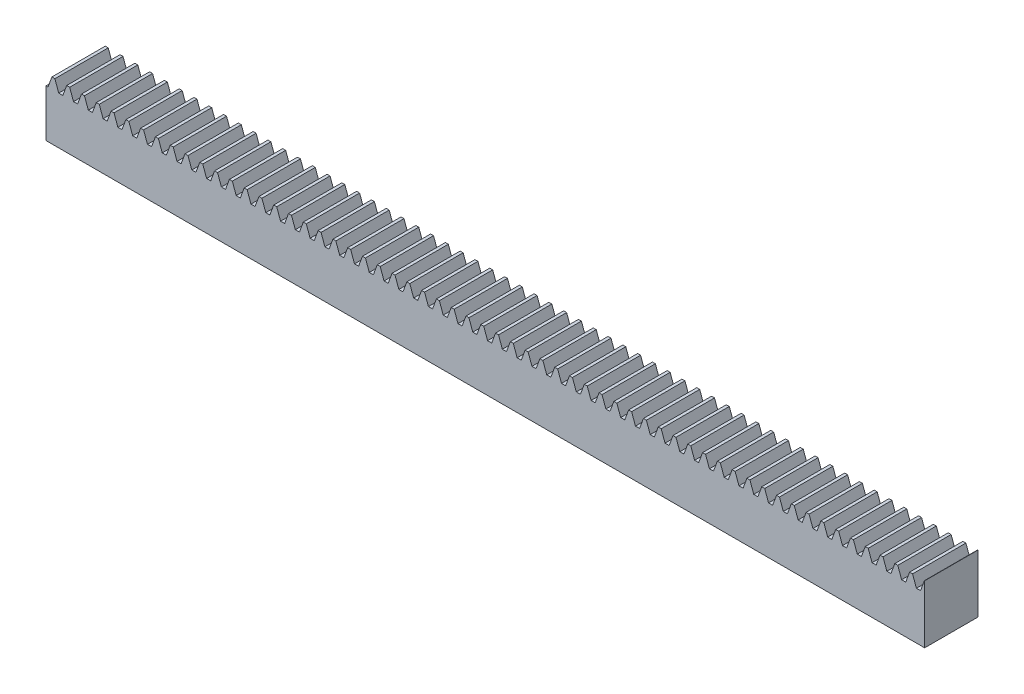
SolidWorks part; units mm, degrees
extrude "Blank" add sketch "BlankSke" against normal blind 17
sketch "BlankSke" plane through (0, 0, 0) normal (0, 0, 1) x (1, 0, 0)
  line L1 (0, 0) -> (280, 0)
  line L2 (0, 0) -> (0, 18.5)
  line L3 (0, 18.5) -> (280, 18.5)
  line L4 (280, 0) -> (280, 18.5)
  dimension "Length" = 280
  dimension "Blank_height" = 18.5
ref_plane "Plane1" through (0, 0, 0) normal (0, 0, 1) x (1, 0, 0)
ref_plane "Plane2" through (0, 0, 0) normal (0, 1, 0) x (1, 0, 0)
ref_plane "Plane3" through (0, 0, 0) normal (1, 0, 0) x (0, 0, -1)
sketch "HoldingSke" plane through (0, 0, 0) normal (0, 1, 0) x (1, 0, 0)
  line L0 (0, 0) -> (0.0928, 0.6602)
  line L1 (-15, 0) -> (100, 0) construction
  line L2 (0, 0) -> (-2.1039, 2.3779)
  line L3 (0, 0) -> (-11.863, 4.5341)
  line L4 (0, 0) -> (4.1868, 7.5532)
  line L5 (0, 0) -> (-23.7986, -8.8762)
  line L6 (0, 0) -> (-10.5278, -7.1032)
  line L9 (-71.009, 38.7566) -> (192.105, 134.5223)
  line L10 (-76.2, 3.8779) -> (-59.2, 3.8779)
  line L11 (0, 0) -> (-17, 0)
  line L12 (-76.2, 101.6) -> (-76.147, 101.6)
  line L13 (24.9733, 27.94) -> (52.9518, 28.4284)
  line L14 (24.9733, 27.94) -> (24.9743, 27.94)
  line L15 (24.9733, 27.94) -> (100.4006, 29.5858)
  circle A0 centre (0, 0) radius 19.05
  circle A1 centre (0, 0) radius 8.5
  circle A2 centre (0, 0) radius 12.7
  dimension "MPH" = 17
  dimension "Diameter" = 38.1
  dimension "Num_teeth" = 61
  dimension "Pitch" = 0.6667
  dimension "Show_teeth" = 998
  dimension "Thickness" = 12.7
  dimension "Ap" = 20
  dimension "Pitch_height" = 17
  dimension "Width" = 17
  dimension "Backlash" = 0.053
  dimension "Addendum_fac" = 1
  dimension "Dedendum_fac" = 1.25
  dimension "Clearance_fac" = 0.25
  dimension "Dedendum_add" = 0.001
  dimension "Length" = 280
  dimension "Module" = 1.5
sketch "TooCutSkeIll" plane through (0, 0, 0) normal (0, 0, 1) x (1, 0, 0)
  line L0 (-1.8687, 18.4605) -> (-0.7447, 15.3724)
  line L1 (-0.3914, 15.125) -> (0.3914, 15.125)
  line L2 (0.7447, 15.3724) -> (1.8687, 18.4605)
  line L3 (280, 18.5) -> (0, 18.5) construction
  line L4 (0, 0) -> (0, 64.897) construction
  line L5 (-13.208, 17) -> (12.954, 17) construction
  line L6 (0, 0) -> (280, 0) construction
  line L7 (1.3371, 17) -> (1.3371, 48.7463) construction
  line L8 (-1.3371, 17) -> (-1.3371, 48.7463) construction
  line L9 (1.9251, 18.5) -> (1.9251, 18.5254)
  line L10 (-1.9251, 18.5) -> (-1.9251, 18.5254)
  line L11 (-1.9251, 18.5254) -> (1.9251, 18.5254)
  arc A0 (0.3914, 15.125) -> (0.7447, 15.3724) centre (0.3914, 15.501) ccw
  arc A1 (-0.7447, 15.3724) -> (-0.3914, 15.125) centre (-0.3914, 15.501) ccw
  arc A2 (1.9251, 18.5) -> (1.8687, 18.4605) centre (1.9251, 18.44) ccw
  arc A3 (-1.8687, 18.4605) -> (-1.9251, 18.5) centre (-1.9251, 18.44) ccw
  dimension "Pitch_height" = 17
  dimension "Addendum_plus" = 1.5254
  dimension "Pressure_angle" = 20
  dimension "Gap_width" = 2.6742
  dimension "Dedendum" = 1.875
extrude "ToothCutIll" [suppressed] cut sketch "TooCutSkeIll" against normal through all
sketch "TooCutSkeSim" plane through (0, 0, 0) normal (0, 0, 1) x (1, 0, 0)
  line L0 (0.6547, 15.125) -> (-0.6547, 15.125)
  line L1 (1.8923, 18.5254) -> (0.6547, 15.125)
  line L2 (0, 17.4625) -> (0, 53.467) construction
  line L3 (1.8923, 18.5254) -> (-1.8923, 18.5254)
  line L6 (-1.8923, 18.5254) -> (-0.6547, 15.125)
  line L9 (-1.3371, 17) -> (1.3371, 17) construction
  line L10 (0, 0) -> (280, 0) construction
  line L11 (1.3371, 17) -> (1.3371, 53.467) construction
  line L12 (-1.3371, 17) -> (-1.3371, 53.467) construction
  dimension "Pitch_height" = 17
  dimension "Addendum_plus" = 1.5254
  dimension "Pressure_angle" = 20
  dimension "Gap_width" = 2.6742
  dimension "Dedendum" = 1.875
extrude "ToothCutSim" cut sketch "TooCutSkeSim" against normal through all
pattern_linear "TeethCuts" count 60 spacing 4.7124 along (1, 0, 0) of "ToothCutIll", "ToothCutSim"
equation "' \"Module@HoldingSke\" = 6.35"
equation "' \"Num_teeth@HoldingSke\" = 12"
equation "' \"Ap@HoldingSke\" =  20"
equation "' \"Ap@HoldingSke\" = 20"
equation "' \"Width@HoldingSke\" = 0.25 * 25.4"
equation "' \"Show_teeth@HoldingSke\" = 500"
equation "' \"Backlash@HoldingSke\" = 0.009 * 25.4"
equation "' \"Addendum_fac@HoldingSke\" = 1.0"
equation "' \"Dedendum_fac@HoldingSke\" = 1.25"
equation "' \"Dedendum_add@HoldingSke\" = 0.00005 * 25.4"
equation "' \"Clearance_fac@HoldingSke\" = 0.25"
equation "' \"Pitch_height@HoldingSke\" = 1 * 25.4"
equation "' \"Length@HoldingSke\" = 4.71 * 25.4"
equation "\"Pitch@HoldingSke\" = 1 / \"Module@HoldingSke\""
equation "\"MPH@HoldingSke\" = \"Dedendum_fac@HoldingSke\" / \"Pitch@HoldingSke\" + 2 * \"Dedendum_add@HoldingSke\" + 0.002 * 25.4"
equation "\"MPH@HoldingSke\" = ((sgn( \"MPH@HoldingSke\" - \"Pitch_height@HoldingSke\")+1)*( \"MPH@HoldingSke\" - \"Pitch_height@HoldingSke\"))/2 + \"Pitch_height@HoldingSke\""
equation "\"Blank_height@BlankSke\" = \"Pitch_height@HoldingSke\" + \"Addendum_fac@HoldingSke\"  / \"Pitch@HoldingSke\" "
equation "\"Length@BlankSke\" =  \"Length@HoldingSke\""
equation "\"Face_width@Blank\" = \"Width@HoldingSke\""
equation "\"Pressure_angle@TooCutSkeIll\" = \"Ap@HoldingSke\""
equation "\"Addendum_plus@TooCutSkeIll\" =  \"Addendum_fac@HoldingSke\"  / \"Pitch@HoldingSke\" + 0.001 *25.4"
equation "\"Dedendum@TooCutSkeIll\" = \"Dedendum_fac@HoldingSke\"  / \"Pitch@HoldingSke\""
equation "\"Pitch_height@TooCutSkeIll\" =  \"MPH@HoldingSke\""
equation "\"Gap_width@TooCutSkeIll\" = 3.14159265 / 2 / \"Pitch@HoldingSke\" + 6 * \"Backlash@HoldingSke\""
equation "\"Pressure_angle@TooCutSkeSim\" = \"Ap@HoldingSke\""
equation "\"Addendum_plus@TooCutSkeSim\" =  \"Addendum_fac@HoldingSke\"  / \"Pitch@HoldingSke\" + 0.001 * 25.4"
equation "\"Dedendum@TooCutSkeSim\" = \"Dedendum_fac@HoldingSke\"  / \"Pitch@HoldingSke\""
equation "\"Pitch_height@TooCutSkeSim\" =  \"MPH@HoldingSke\""
equation "\"Gap_width@TooCutSkeSim\" = 3.14159265 / 2 / \"Pitch@HoldingSke\" + 6 * \"Backlash@HoldingSke\""
equation "\"Root_fillet@TooCutSkeIll\" = \"Clearance_fac@HoldingSke\" / \"Pitch@HoldingSke\" + \"Dedendum_add@HoldingSke\""
equation "\"Break_rad@TooCutSkeIll\" = 0.02 / \"Pitch@HoldingSke\" * 2"
equation "\"Linear_pitch@TeethCuts\" = 3.14159265 / \"Pitch@HoldingSke\""
equation "\"Num_teeth@HoldingSke\" = int( ( \"Length@HoldingSke\" + 0 ) / (3.14159265 / \"Pitch@HoldingSke\")) + 0.9999  + 1"
equation " \"Num_teeth@TeethCuts\" = int( \"Show_teeth@HoldingSke\" ) + 1"
equation " \"Num_teeth@TeethCuts\" = ((sgn( \"Num_teeth@TeethCuts\" - \"Num_teeth@HoldingSke\" )-1)*( \"Num_teeth@TeethCuts\" - \"Num_teeth@HoldingSke\" ))/-2+ \"Num_teeth@HoldingSke\""
equation " \"Num_teeth@TeethCuts\" = ((sgn( \"Num_teeth@TeethCuts\" - 2.0)+1)*( \"Num_teeth@TeethCuts\" - 2.0))/2 +2.0"
